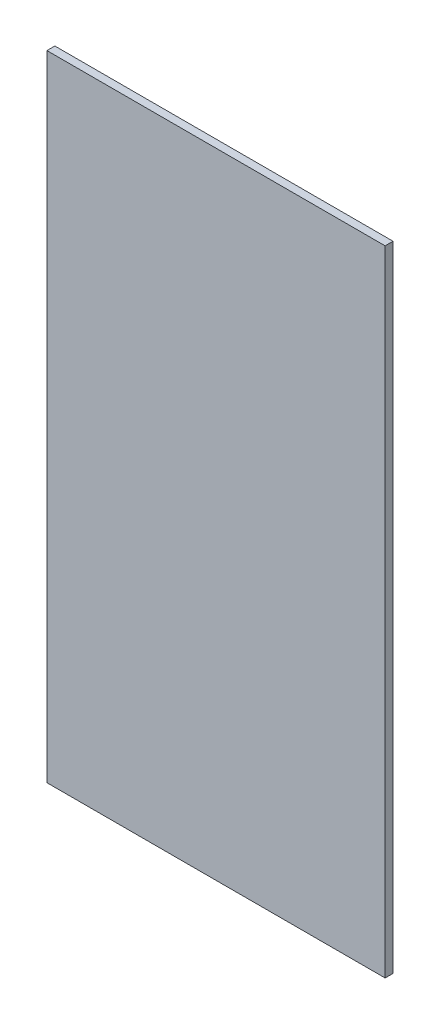
SolidWorks part; units mm, degrees
ref_plane "Front Plane" through (0, 0, 0) normal (0, 0, 1) x (1, 0, 0)
ref_plane "Top Plane" through (0, 0, 0) normal (0, 1, 0) x (1, 0, 0)
ref_plane "Right Plane" through (0, 0, 0) normal (1, 0, 0) x (0, 0, -1)
sketch "Sketch1" plane through (0, 0, 0) normal (0, 0, 1) x (1, 0, 0)
  line L0 (1980.232, 418.9405) -> (2793.032, 418.9405)
  line L1 (2793.032, 418.9405) -> (2793.032, 1942.9405)
  line L2 (2793.032, 1942.9405) -> (1980.232, 1942.9405)
  line L3 (1980.232, 1942.9405) -> (1980.232, 418.9405)
extrude "Boss-Extrude1" add sketch "Sketch1" along normal blind 19.05
